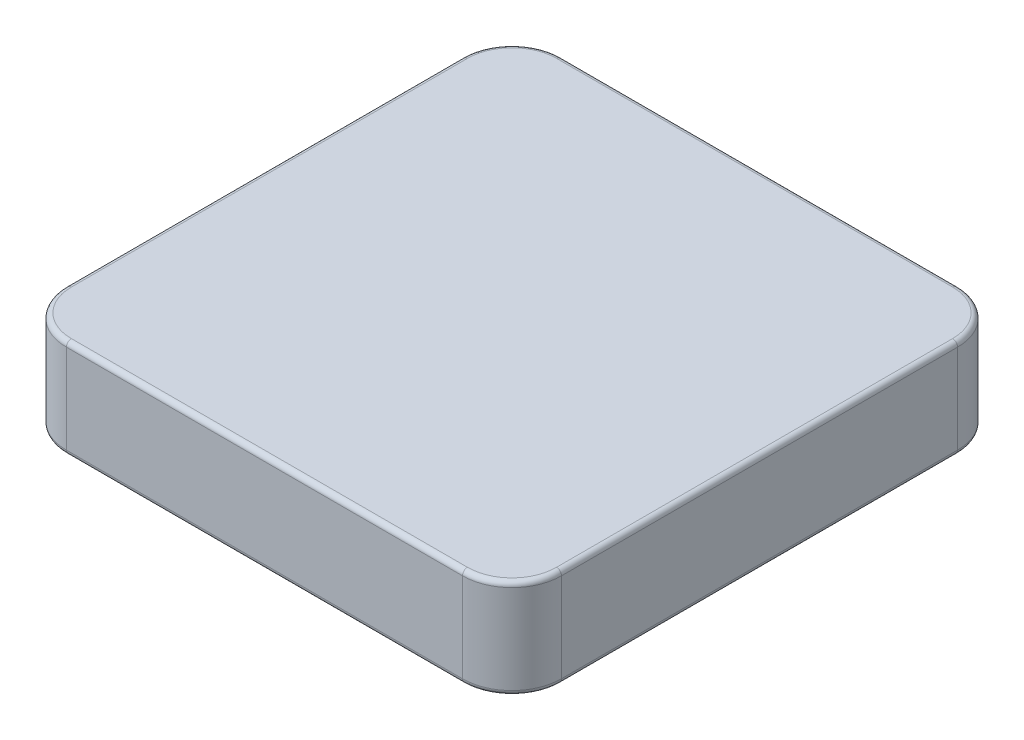
SolidWorks part; units mm, degrees
material "AISI 1035 Steel (SS)"
ref_plane "Front Plane" through (0, 0, 0) normal (0, 0, 1) x (1, 0, 0)
ref_plane "Top Plane" through (0, 0, 0) normal (0, 1, 0) x (1, 0, 0)
ref_plane "Right Plane" through (0, 0, 0) normal (1, 0, 0) x (0, 0, -1)
sketch "Sketch1" plane through (0, 0, 0) normal (0, 1, 0) x (1, 0, 0)
  line L1 (10, 0) -> (90, 0)
  line L2 (0, -10) -> (0, -90)
  line L3 (10, -100) -> (90, -100)
  line L4 (100, -10) -> (100, -90)
  arc A0 (10, -100) -> (0, -90) centre (10, -90) cw
  arc A1 (90, -100) -> (100, -90) centre (90, -90) ccw
  arc A2 (100, -10) -> (90, 0) centre (90, -10) ccw
  arc A3 (10, 0) -> (0, -10) centre (10, -10) ccw
  point P13 (0, 0)
  dimension "D1" = 10
extrude "Boss-Extrude1" add sketch "Sketch1" along normal mid plane 20
fillet "Fillet1" radius 1 8 edges at (97.0711, -10, 97.0711) (50, -10, 100) (2.9289, -10, 97.0711) (0, -10, 50) (2.9289, -10, 2.9289) (50, -10, 0) (97.0711, -10, 2.9289) (100, -10, 50)
fillet "Fillet2" radius 1 8 edges at (50, 10, 100) (2.9289, 10, 97.0711) (0, 10, 50) (2.9289, 10, 2.9289) (50, 10, 0) (97.0711, 10, 2.9289) (100, 10, 50) (97.0711, 10, 97.0711)
ref_plane "Plane1" through (0, 0, 50) normal (0, 0, 1) x (1, 0, 0)
ref_plane "Plane2" through (50, 0, 0) normal (-1, 0, 0) x (0, 0, 1)
